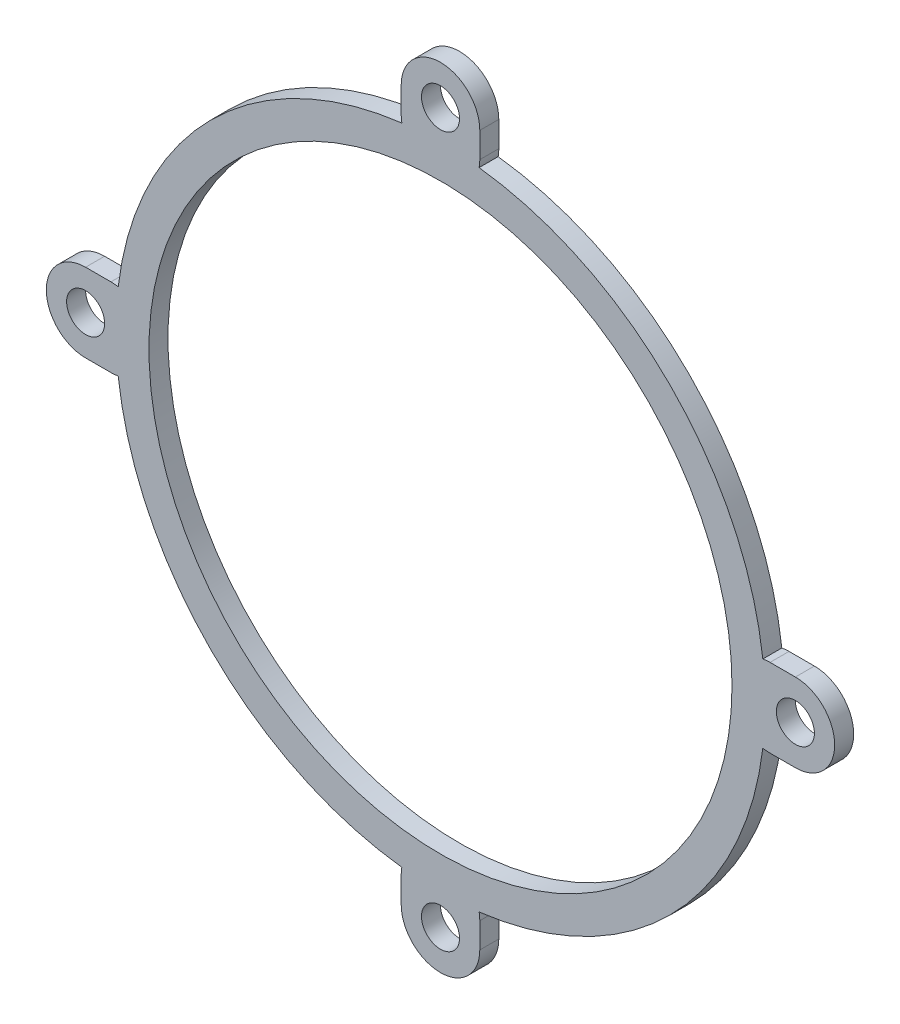
SolidWorks part; units mm, degrees
ref_plane "Front Plane" through (0, 0, 0) normal (0, 0, 1) x (1, 0, 0)
ref_plane "Top Plane" through (0, 0, 0) normal (0, 1, 0) x (1, 0, 0)
ref_plane "Right Plane" through (0, 0, 0) normal (1, 0, 0) x (0, 0, -1)
sketch "Sketch2" plane through (0, 0, 0) normal (0, 0, 1) x (1, 0, 0)
  line L0 (26, -3.1) -> (28, -3.1)
  line L1 (28, 3.1) -> (26, 3.1)
  line L2 (3.1, 26) -> (3.1, 28)
  line L3 (-3.1, 28) -> (-3.1, 26)
  line L4 (-26, 3.1) -> (-28, 3.1)
  line L5 (-28, -3.1) -> (-26, -3.1)
  line L6 (-3.1, -26) -> (-3.1, -28)
  line L7 (3.1, -28) -> (3.1, -26)
  circle A0 centre (0, 0) radius 23
  circle A1 centre (-28, 0) radius 1.5
  circle A2 centre (0, 28) radius 1.5
  circle A3 centre (28, 0) radius 1.5
  circle A4 centre (0, -28) radius 1.5
  arc A5 (3.047, -25.429) -> (25.429, -3.047) centre (0, 0) ccw
  arc A6 (25.429, -3.047) -> (26, -3.1) centre (26, 0) ccw
  arc A7 (28, -3.1) -> (28, 3.1) centre (28, 0) ccw
  arc A8 (26, 3.1) -> (25.429, 3.047) centre (26, 0) ccw
  arc A9 (25.429, 3.047) -> (3.047, 25.429) centre (0, 0) ccw
  arc A10 (3.047, 25.429) -> (3.1, 26) centre (0, 26) ccw
  arc A11 (3.1, 28) -> (-3.1, 28) centre (0, 28) ccw
  arc A12 (-3.1, 26) -> (-3.047, 25.429) centre (0, 26) ccw
  arc A13 (-3.047, 25.429) -> (-25.429, 3.047) centre (0, 0) ccw
  arc A14 (-25.429, 3.047) -> (-26, 3.1) centre (-26, 0) ccw
  arc A15 (-28, 3.1) -> (-28, -3.1) centre (-28, 0) ccw
  arc A16 (-26, -3.1) -> (-25.429, -3.047) centre (-26, 0) ccw
  arc A17 (-25.429, -3.047) -> (-3.047, -25.429) centre (0, 0) ccw
  arc A18 (-3.047, -25.429) -> (-3.1, -26) centre (0, -26) ccw
  arc A19 (-3.1, -28) -> (3.1, -28) centre (0, -28) ccw
  arc A20 (3.1, -26) -> (3.047, -25.429) centre (0, -26) ccw
extrude "Boss-Extrude1" add sketch "Sketch2" along normal blind 1.5
